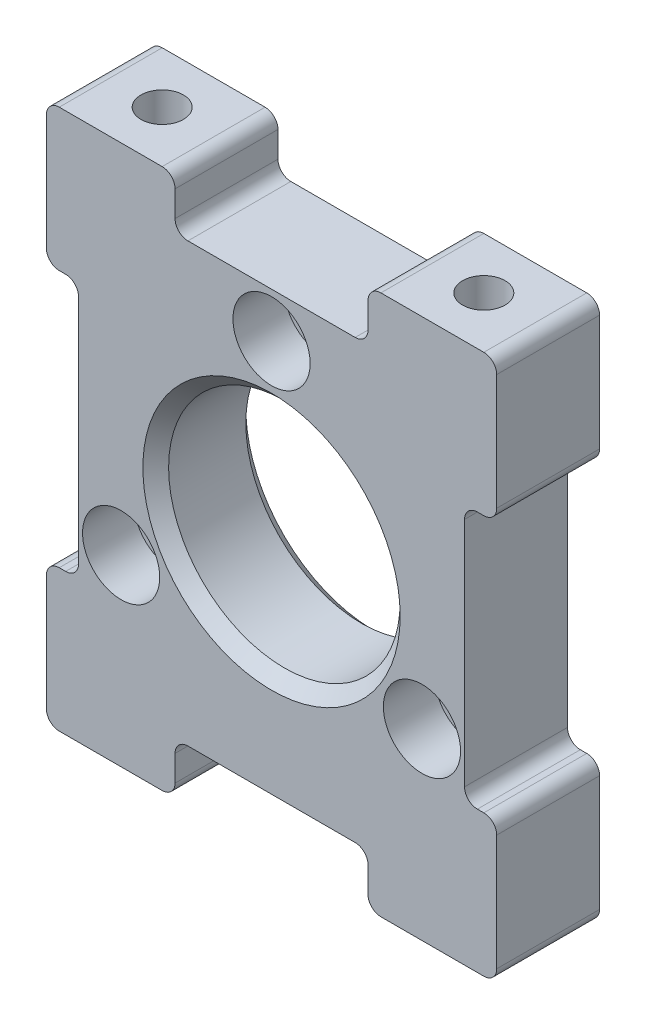
SolidWorks part; units mm, degrees
material "6061 合金"
ref_plane "前视基准面" through (0, 0, 0) normal (0, 0, 1) x (1, 0, 0)
ref_plane "上视基准面" through (0, 0, 0) normal (0, 1, 0) x (1, 0, 0)
ref_plane "右视基准面" through (0, 0, 0) normal (1, 0, 0) x (0, 0, -1)
sketch "草图1" plane through (0, 0, 0) normal (0, 0, 1) x (1, 0, 0)
  line L1 (-17.5, 21) -> (17.5, 21)
  line L2 (-17.5, 21) -> (-17.5, -21)
  line L3 (-17.5, -21) -> (17.5, -21)
  line L4 (17.5, 21) -> (17.5, -21)
  line L5 (-17.5, 21) -> (17.5, -21) construction
  line L6 (-17.5, -21) -> (17.5, 21) construction
  point P0 (0, 0)
  dimension "D1" = 35
  dimension "D2" = 42
extrude "凸台-拉伸1" add sketch "草图1" along normal mid plane 8
sketch "草图2" plane through (0, 0, 4) normal (0, 0, 1) x (1, 0, 0)
  circle A0 centre (0, 0) radius 13.5 construction
  circle A1 centre (0, 13.5) radius 1.5
  circle A2 centre (11.6913, -6.75) radius 1.5
  circle A3 centre (-11.6913, -6.75) radius 1.5
  circle A4 centre (0, 0) radius 9
  point P11 (0, 0)
  dimension "D1" = 27
  dimension "D2" = 3
  dimension "D3" = 3
  dimension "D4" = 18
extrude "切除-拉伸1" cut sketch "草图2" against normal blind 8
sketch "草图3" plane through (0, 0, 4) normal (0, 0, 1) x (1, 0, 0)
  circle A1 centre (-11.6913, -6.75) radius 1.5 construction
  circle A2 centre (11.6913, -6.75) radius 1.5 construction
  circle A3 centre (0, 13.5) radius 1.5 construction
  circle A4 centre (-11.6913, -6.75) radius 1.5 construction
  circle A5 centre (11.6913, -6.75) radius 1.5 construction
  circle A6 centre (0, 13.5) radius 1.5 construction
  circle A7 centre (-11.6913, -6.75) radius 3
  circle A8 centre (11.6913, -6.75) radius 3
  circle A9 centre (0, 13.5) radius 3
  dimension "D1" = 1.5
extrude "切除-拉伸2" cut sketch "草图3" against normal blind 4
sketch "草图5" plane through (0, 21, 0) normal (0, 1, 0) x (1, 0, 0)
  line L0 (-12.5, 0) -> (12.5, 0) construction
  point P3 (0, 0)
  dimension "D1" = 25
sketch "草图6" [suppressed] plane through (0, 0, 4) normal (0, 0, 1) x (1, 0, 0)
  line L0 (17.5, -21) -> (17.5, 21) construction
  line L1 (-17.5, 21) -> (17.5, 21)
  line L2 (-17.5, 21) -> (-17.5, 13)
  line L3 (-17.5, 13) -> (17.5, 13)
  line L4 (17.5, 21) -> (17.5, 13)
  line L5 (-17.5, 21) -> (-17.5, -21) construction
  line L6 (17.5, -21) -> (-17.5, -21)
  line L7 (17.5, -21) -> (17.5, -13)
  line L8 (17.5, -13) -> (-17.5, -13)
  line L9 (-17.5, -21) -> (-17.5, -13)
  line L10 (-7.5, 17.5) -> (-7.5, -21)
  line L11 (-7.5, 24.5) -> (7.5, 24.5)
  line L12 (-7.5, 24.5) -> (-7.5, 17.5)
  line L13 (-7.5, 17.5) -> (7.5, 17.5)
  line L14 (7.5, 24.5) -> (7.5, 17.5)
  line L15 (-7.5, 24.5) -> (7.5, 17.5) construction
  line L16 (-7.5, 17.5) -> (7.5, 24.5) construction
  line L17 (7.5, 17.5) -> (7.5, -21)
  line L18 (-17.5, 0) -> (17.5, 0)
  line L19 (17.5, 0) -> (17.5, 13)
  line L20 (-17.5, 0) -> (-17.5, 13)
  circle A0 centre (0, 0) radius 15
  point P14 (0, 21)
  dimension "D4" = 30
  dimension "D1" = 8
  dimension "D2" = 15
  dimension "D3" = 7
hole_wizard "M4 螺纹孔1" positions "草图7" profile "草图8" tap size "M4" standard "ISO"
sketch "草图7" plane through (0, 21, 0) normal (0, 1, 0) x (1, 0, 0)
  point P0 (-12.5, 0)
  point P3 (12.5, 0)
sketch "草图8" plane through (-12.5, 21, 0) normal (1, 0, 0) x (0, 0, 1)
  line L0 (0, 0) -> (0, 10.9914)
  line L1 (0, 10.9914) -> (1.65, 10)
  line L2 (1.65, 10) -> (1.65, 0)
  line L5 (1.65, 0) -> (0, 0)
  line L10 (0, 10.9914) -> (-1.65, 10) construction
  line L11 (0, -6.35) -> (0, 107.95) construction
  dimension "螺纹孔钻头直径" = 3.3
  dimension "螺纹孔钻头深度" = 10
  dimension "导头角度" = 118
cosmetic thread "孔螺蚊线1" parameters "D1"=42, "D2"=4
cosmetic thread "孔螺蚊线2" parameters "D1"=42, "D2"=4
mirror "镜向1" about plane through (0, 0, 0) normal (0, 1, 0) of "M4 螺纹孔1"
sketch "草图9" plane through (0, 0, -4) normal (0, 0, -1) x (-1, 0, 0)
  circle A0 centre (0, 0) radius 12.15 construction
  circle A1 centre (0, -12.15) radius 2
  circle A2 centre (-10.5222, 6.075) radius 2
  circle A3 centre (10.5222, 6.075) radius 2
  point P5 (15.3662, 8.3181)
  point P6 (0, 0)
  point P12 (0, 0)
  dimension "D1" = 24.3
  dimension "D2" = 4
  dimension "D3" = 3
extrude "切除-拉伸3" cut sketch "草图9" against normal blind 5.1
sketch "草图10" plane through (0, 0, -4) normal (0, 0, -1) x (-1, 0, 0)
  line L0 (12.5, 21) -> (-12.5, 21) construction
  line L1 (-7.5, 25) -> (7.5, 25)
  line L2 (-7.5, 25) -> (-7.5, 17)
  line L3 (-7.5, 17) -> (7.5, 17)
  line L4 (7.5, 25) -> (7.5, 17)
  line L5 (-7.5, 25) -> (7.5, 17) construction
  line L6 (-7.5, 17) -> (7.5, 25) construction
  line L7 (17.5, -21) -> (-17.5, -21) construction
  line L8 (-7.5, -25) -> (7.5, -25)
  line L9 (-7.5, -25) -> (-7.5, -17)
  line L10 (-7.5, -17) -> (7.5, -17)
  line L11 (7.5, -25) -> (7.5, -17)
  line L12 (-7.5, -25) -> (7.5, -17) construction
  line L13 (-7.5, -17) -> (7.5, -25) construction
  line L14 (17.5, 21) -> (17.5, -21) construction
  line L15 (15, 10) -> (20, 10)
  line L16 (15, 10) -> (15, -10)
  line L17 (15, -10) -> (20, -10)
  line L18 (20, 10) -> (20, -10)
  line L19 (15, 10) -> (20, -10) construction
  line L20 (15, -10) -> (20, 10) construction
  line L21 (-17.5, -21) -> (-17.5, 21) construction
  line L22 (-20, 10) -> (-15, 10)
  line L23 (-20, 10) -> (-20, -10)
  line L24 (-20, -10) -> (-15, -10)
  line L25 (-15, 10) -> (-15, -10)
  line L26 (-20, 10) -> (-15, -10) construction
  line L27 (-20, -10) -> (-15, 10) construction
  point P0 (0, 21)
  point P7 (0, -21)
  point P14 (17.5, 0)
  point P21 (-17.5, 0)
  dimension "D1" = 15
  dimension "D2" = 8
  dimension "D3" = 5
  dimension "D4" = 20
extrude "切除-拉伸4" cut sketch "草图10" against normal through all and the other way through all
fillet "圆角2" radius 1 20 edges at (-17.5, 21, 0) (-17.5, 10, 0) (-15, 10, 0) (-15, -10, 0) (-17.5, -10, 0) (-17.5, -21, 0) (-7.5, -21, 0) (-7.5, -17, 0) (7.5, -17, 0) (7.5, -21, 0) (17.5, -21, 0) (17.5, -10, 0) (15, -10, 0) (15, 10, 0) (17.5, 10, 0) (17.5, 21, 0) (-7.5, 17, 0) (-7.5, 21, 0) (7.5, 21, 0) (7.5, 17, 0)
chamfer "倒角1" distance 1 angle 45 2 edges at (9, 0, 4) (9, 0, -4)
